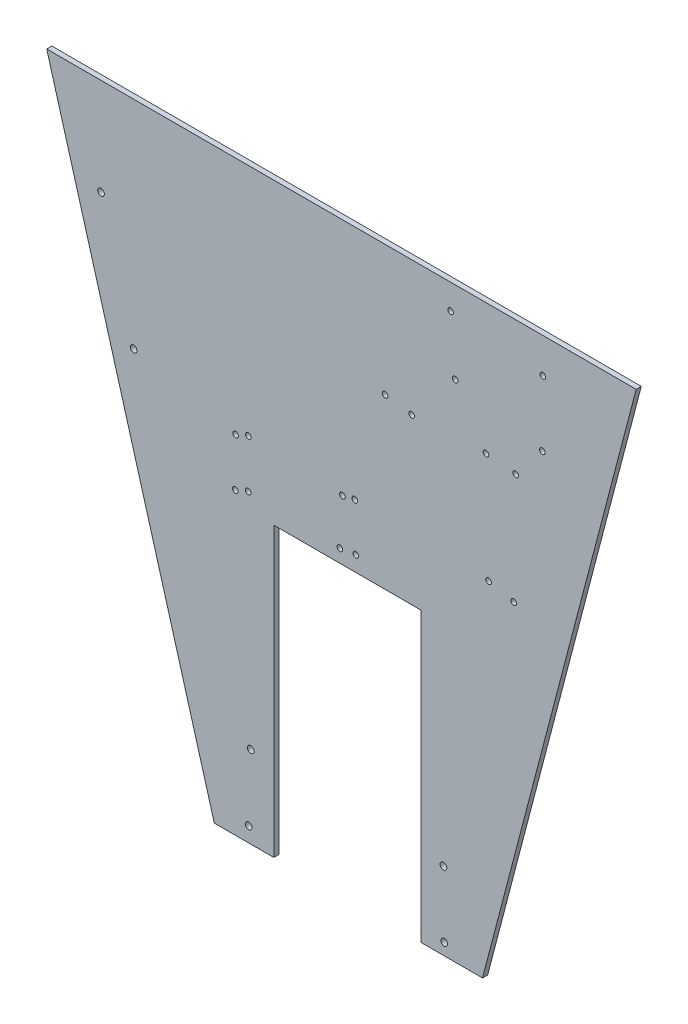
SolidWorks part; units mm, degrees
ref_plane "Front Plane" through (0, 0, 0) normal (0, 0, 1) x (1, 0, 0)
ref_plane "Top Plane" through (0, 0, 0) normal (0, 1, 0) x (1, 0, 0)
ref_plane "Right Plane" through (0, 0, 0) normal (1, 0, 0) x (0, 0, -1)
sketch "Sketch1" plane through (0, 0, 0) normal (0, 0, 1) x (1, 0, 0)
  line L0 (0, 210) -> (0, 0)
  line L1 (0, 0) -> (230, 0)
  line L2 (230, 0) -> (285, 210)
  line L3 (285, 210) -> (0, 210)
  circle A0 centre (104, 185.5) radius 2.75
  circle A1 centre (194, 176) radius 2.75
  circle A2 centre (108.5, 130) radius 2.75
  circle A3 centre (193.5, 112) radius 2.75
  circle A4 centre (138.5, 82.5) radius 2.75
  circle A5 centre (167.5, 79.5) radius 2.75
  circle A6 centre (40, 83) radius 2.75
  circle A7 centre (66, 79) radius 2.75
  dimension "D4" = 5.5
  dimension "D6" = 26
  dimension "D7" = 72.5
  dimension "D8" = 29
  dimension "D9" = 26
  dimension "D11" = 90
  dimension "D12" = 24.5
  dimension "D13" = 34
  dimension "D15" = 0.5
  dimension "D14" = 64
  dimension "D16" = 55.5
  dimension "D17" = 79.5
  dimension "D18" = 82.5
  dimension "D19" = 79
  dimension "D20" = 83
  dimension "D1" = 230
  dimension "D2" = 285
  dimension "D3" = 210
  dimension "D5" = 40
  dimension "D10" = 85
extrude "Boss-Extrude1" add sketch "Sketch1" along normal blind 5
sketch "Sketch2" plane through (0, 0, 0) normal (0, 0, 1) x (1, 0, 0)
  line L0 (0, 0) -> (0, 210)
  line L1 (0, 210) -> (-290, 210)
  line L2 (-290, 210) -> (-230, 0)
  line L3 (-230, 0) -> (0, 0)
  line L4 (-237, 115.5) -> (-263, 115.5) construction
  line L5 (-205.2143, -1) -> (-229.7143, -1) construction
  line L6 (-229.7143, -1) -> (-230, 0) construction
  circle A0 centre (-237, 115.5) radius 3.25
  circle A1 centre (-205.2143, -1) radius 3.25
  dimension "D3" = 6.5
  dimension "D4" = 94.5
  dimension "D5" = 1
  dimension "D1" = 290
  dimension "D2" = 230
  dimension "D6" = 26
  dimension "D7" = 24.5
extrude "Boss-Extrude2" add sketch "Sketch2" along normal blind 5 contours A1 L3 L0 L1 L2 A0
sketch "Sketch3" plane through (0, 0, 0) normal (0, 0, 1) x (1, 0, 0)
  line L0 (-230, 0) -> (-170, -210)
  line L1 (-170, -210) -> (0, -210)
  line L2 (0, -210) -> (0, 0)
  line L3 (0, 0) -> (-230, 0)
  line L4 (-290, 210) -> (-230, 0) construction
  line L5 (-68.5, -81.5) -> (-68.5, -210)
  line L6 (-68.5, -81.5) -> (0, -81.5)
  circle A0 centre (-205.2143, -1) radius 3.25
  arc A1 (-202.122, 0) -> (-208.3066, 0) centre (-205.2143, -1) ccw construction
  circle A2 centre (-93.25, -18.5) radius 2.75
  circle A3 centre (-93.5, -65.5) radius 2.75
  circle A4 centre (-105.75, -23.5) radius 2.75
  circle A5 centre (-106, -70.5) radius 2.75
  circle A6 centre (-4, -68.75) radius 2.75
  circle A7 centre (-1.5, -23) radius 2.75
  dimension "D2" = 5.5
  dimension "D3" = 18.5
  dimension "D4" = 23.5
  dimension "D5" = 65.5
  dimension "D6" = 70.5
  dimension "D8" = 23
  dimension "D11" = 93.25
  dimension "D12" = 93.5
  dimension "D14" = 1.5
  dimension "D16" = 81.5
  dimension "D1" = 210
  dimension "D7" = 68.75
  dimension "D9" = 12.5
  dimension "D10" = 12.5
  dimension "D13" = 4
  dimension "D15" = 68.5
extrude "Boss-Extrude3" add sketch "Sketch3" along normal blind 5 contours A7 L2 L3 A0 L0 L1 L5 L6 A6 A5 A4 A3 A2
sketch "Sketch4" plane through (0, 0, 0) normal (0, 0, 1) x (1, 0, 0)
  line L0 (-170, -210) -> (-126.5, -362.25)
  line L1 (-126.5, -362.25) -> (-68.5, -362.25)
  line L2 (-68.5, -362.25) -> (-68.5, -210)
  line L3 (-170, -210) -> (-68.5, -210) construction
  line L4 (-68.5, -81.5) -> (-68.5, -210) construction
  line L5 (-290, 210) -> (-170, -210) construction
  line L6 (-170, -210) -> (-68.5, -210)
  circle A0 centre (-93, -347.75) radius 3.25
  circle A1 centre (-91, -282.25) radius 3.25
  dimension "D2" = 6.5
  dimension "D3" = 22.5
  dimension "D4" = 24.5
  dimension "D5" = 80
  dimension "D6" = 14.5
  dimension "D1" = 58
extrude "Boss-Extrude4" add sketch "Sketch4" along normal blind 5
sketch "Sketch5" plane through (0, 0, 0) normal (0, 0, 1) x (1, 0, 0)
  line L0 (0, 0) -> (0, -210)
  line L1 (0, -210) -> (175, -210)
  line L2 (175, -210) -> (230, 0)
  line L3 (230, 0) -> (0, 0)
  line L4 (230, 0) -> (285, 210) construction
  line L5 (0, -81.5) -> (75, -81.5)
  line L6 (75, -81.5) -> (75, -210)
  circle A0 centre (-1.5, -23) radius 2.75
  circle A1 centre (-4, -68.75) radius 2.75
  circle A2 centre (10.5, -20.5) radius 2.75
  circle A3 centre (11.5, -66.5) radius 2.75
  circle A4 centre (141, -24) radius 2.75
  circle A5 centre (165.5, -29.5) radius 2.75
  arc A6 (0, -20.6951) -> (0, -25.3049) centre (-1.5, -23) ccw construction
  circle A7 centre (-4, -68.75) radius 2.75 construction
  dimension "D4" = 11.5
  dimension "D5" = 141
  dimension "D6" = 24.5
  dimension "D7" = 29.5
  dimension "D8" = 24
  dimension "D9" = 20.5
  dimension "D10" = 66.5
  dimension "D1" = 210
  dimension "D2" = 75
  dimension "D3" = 10.5
extrude "Boss-Extrude5" add sketch "Sketch5" along normal blind 5 contours A0 L0 L5 L6 L1 L2 L3 A5 A4 A3 A2
sketch "Sketch6" plane through (0, 0, 0) normal (0, 0, 1) x (1, 0, 0)
  line L0 (75, -210) -> (75, -362.25)
  line L1 (75, -362.25) -> (135.125, -362.25)
  line L2 (135.125, -362.25) -> (175, -210)
  line L3 (175, -210) -> (75, -210)
  line L4 (175, -210) -> (285, 210) construction
  line L5 (-126.5, -362.25) -> (-68.5, -362.25) construction
  circle A0 centre (97.75, -350.75) radius 3.25
  circle A1 centre (97, -286.75) radius 3.25
  circle A2 centre (-91, -282.25) radius 3.25 construction
  dimension "D1" = 22.75
  dimension "D2" = 22
  dimension "D3" = 75.5
  dimension "D4" = 11.5
extrude "Boss-Extrude6" add sketch "Sketch6" along normal blind 5
